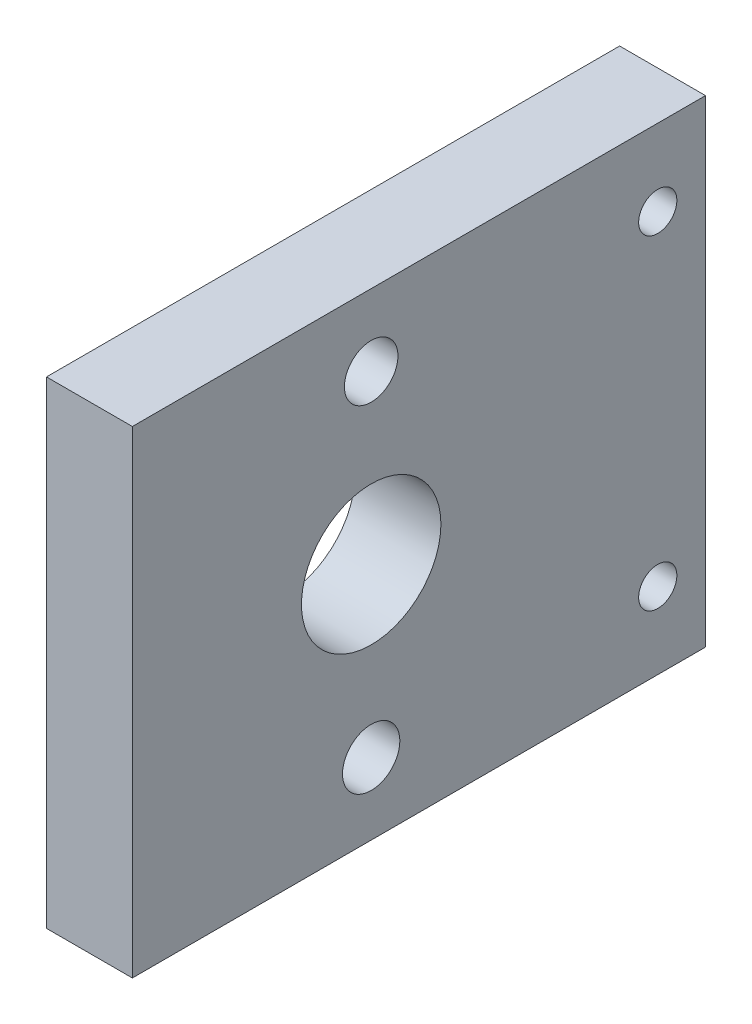
SolidWorks part; units mm, degrees
ref_plane "Plano frontal" through (0, 0, 0) normal (0, 0, 1) x (1, 0, 0)
ref_plane "Plano superior" through (0, 0, 0) normal (0, 1, 0) x (1, 0, 0)
ref_plane "Plano direito" through (0, 0, 0) normal (1, 0, 0) x (0, 0, -1)
sketch "Esboço5" plane through (0, 0, 5) normal (0, 0, 1) x (1, 0, 0)
  line L1 (-52.8109, 50.4855) -> (-48.3154, 50.4855)
  line L2 (-52.8109, 50.4855) -> (-52.8109, 25.4855)
  line L3 (-52.8109, 25.4855) -> (-48.3154, 25.4855)
  line L4 (-48.3154, 50.4855) -> (-48.3154, 25.4855)
extrude "Ressalto-extrusão2" add sketch "Esboço5" along normal blind 25 and the other way blind 5 separate body
sketch "Esboço6" plane through (-52.8109, 0, 0) normal (-1, 0, 0) x (0, 0, 1)
  line L0 (0, 50.4855) -> (5, 50.4855) construction
  line L1 (0, 50.4855) -> (0, 25.4855) construction
  circle A0 centre (2.5, 46.4855) radius 1
  point P4 (2.5, 50.4855)
  dimension "D1" = 4
  dimension "D2" = 2.5
extrude "Corte-extrusão3" cut sketch "Esboço6" against normal blind 10
sketch "Esboço7" plane through (-52.8109, 0, 0) normal (-1, 0, 0) x (0, 0, 1)
  line L0 (0, 25.4855) -> (5, 25.4855) construction
  line L1 (0, 50.4855) -> (0, 25.4855) construction
  circle A0 centre (2.5, 29.4855) radius 1
  point P4 (2.5, 25.4855)
  dimension "D1" = 4
  dimension "D2" = 2.5
extrude "Corte-extrusão4" cut sketch "Esboço7" against normal blind 10
sketch "Esboço8" plane through (-48.3154, 0, 0) normal (1, 0, 0) x (0, 0, -1)
  line L0 (0, 50.4855) -> (-30, 50.4855) construction
  line L1 (-30, 25.4855) -> (-30, 50.4855) construction
  circle A0 centre (-17.5, 37.9855) radius 3.65
  dimension "D1" = 12.5
  dimension "D2" = 12.5
extrude "Corte-extrusão5" cut sketch "Esboço8" against normal blind 10
sketch "Esboço9" plane through (-52.8109, 0, 0) normal (-1, 0, 0) x (0, 0, 1)
  line L1 (30, 50.4855) -> (30, 25.4855) construction
  circle A0 centre (17.5, 46.7355) radius 1.4
  circle A1 centre (17.5, 37.9855) radius 3.65 construction
  dimension "D1" = 8.75
  dimension "D2" = 12.5
extrude "Corte-extrusão6" cut sketch "Esboço9" against normal blind 10
sketch "Esboço10" plane through (-52.8109, 0, 0) normal (-1, 0, 0) x (0, 0, 1)
  line L0 (30, 50.4855) -> (30, 25.4855) construction
  circle A0 centre (17.5, 29.2355) radius 1.5
  circle A1 centre (17.5, 37.9855) radius 3.65 construction
  dimension "D1" = 8.75
  dimension "D2" = 12.5
extrude "Corte-extrusão7" cut sketch "Esboço10" against normal blind 10
